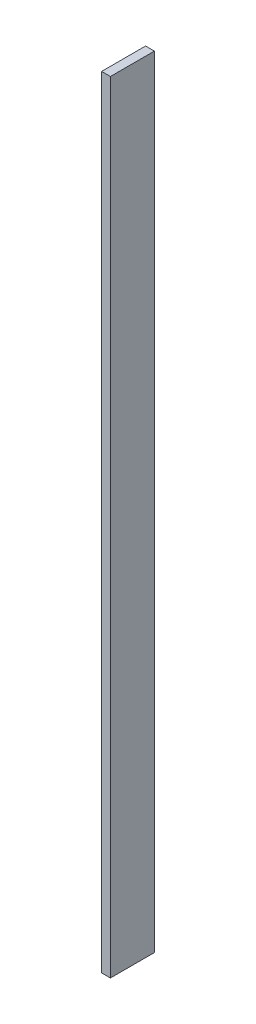
SolidWorks part; units mm, degrees
ref_plane "Front" through (0, 0, 0) normal (0, 0, 1) x (1, 0, 0)
ref_plane "Top" through (0, 0, 0) normal (0, 1, 0) x (1, 0, 0)
ref_plane "Right" through (0, 0, 0) normal (1, 0, 0) x (0, 0, -1)
sketch "Sketch1" plane through (0, 0, 0) normal (0, 1, 0) x (1, 0, 0)
  line L1 (-9.9715, -25.104) -> (0.1885, -25.104)
  line L2 (-9.9715, -25.104) -> (-9.9715, 25.696)
  line L3 (-9.9715, 25.696) -> (0.1885, 25.696)
  line L4 (0.1885, -25.104) -> (0.1885, 25.696)
  line L5 (-9.9715, -25.104) -> (0.1885, 25.696) construction
  line L6 (-9.9715, 25.696) -> (0.1885, -25.104) construction
  point P0 (-4.8915, 0.296)
extrude "Boss-Extrude1" add sketch "Sketch1" along normal blind 901.7
